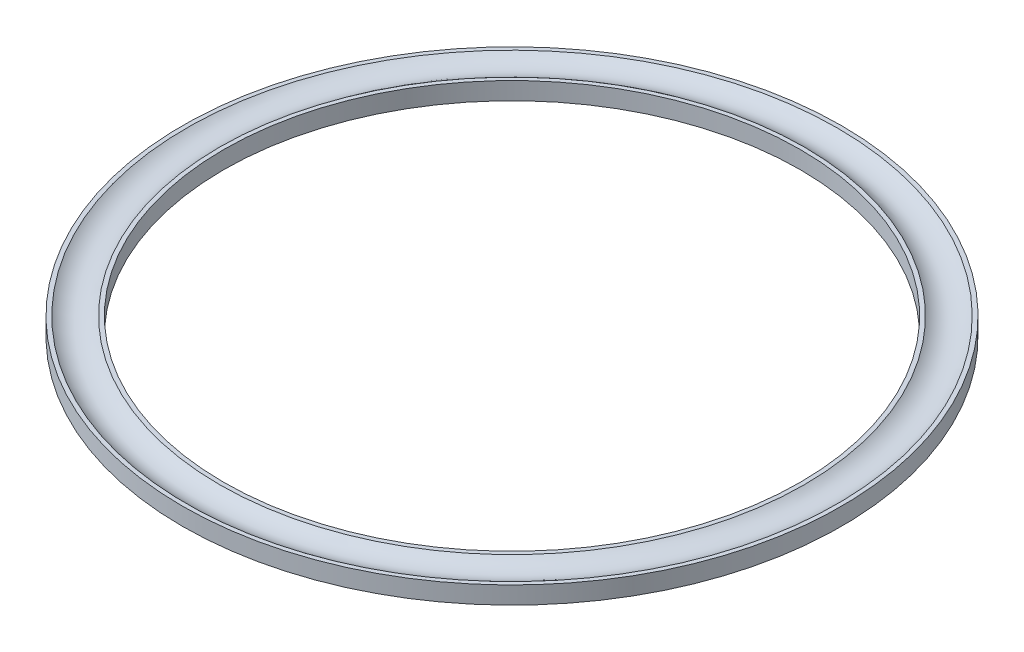
SolidWorks part; units mm, degrees
ref_plane "Front" through (0, 0, 0) normal (0, 0, 1) x (1, 0, 0)
ref_plane "Top" through (0, 0, 0) normal (0, 1, 0) x (1, 0, 0)
ref_plane "Right" through (0, 0, 0) normal (1, 0, 0) x (0, 0, -1)
sketch "Sketch1" plane through (0, 0, 0) normal (0, 0, 1) x (1, 0, 0)
  line L0 (-20.9169, 0) -> (20.9169, 0) construction
  line L1 (23.9141, -0.635) -> (23.9141, 0.635)
  line L2 (23.9141, 0.635) -> (20.9169, 0.635) construction
  line L3 (0, -11.4126) -> (0, 23.1775) construction
  line L4 (0, -0.6845) -> (0, 0.6845) construction
  line L5 (20.9169, 0.635) -> (21.2166, 0.635)
  line L6 (23.9141, -0.635) -> (20.9169, -0.635)
  line L7 (20.9169, 0.635) -> (20.9169, -0.635)
  line L8 (23.9141, 0.635) -> (23.6144, 0.635)
  arc A0 (21.2166, 0.635) -> (23.6144, 0.635) centre (22.4155, 2.0401) ccw
  point P4 (20.9169, 0)
  point P13 (22.4155, 0.193)
  dimension "D1" = 0.442
  dimension "D2" = 0.2997
revolve "Revolve2" add sketch "Sketch1" angle 360 about L3
sketch "Sketch3" plane through (0, -0.635, 0) normal (0, -1, 0) x (1, 0, 0)
  line L0 (20.9169, 0) -> (-20.9169, 0) construction
  circle A0 centre (0, 0) radius 20.9169 construction
  dimension "D1" = 41.8338
equation "\"D2@Sketch1\" = \"Wd@Sketch1\"/10"
